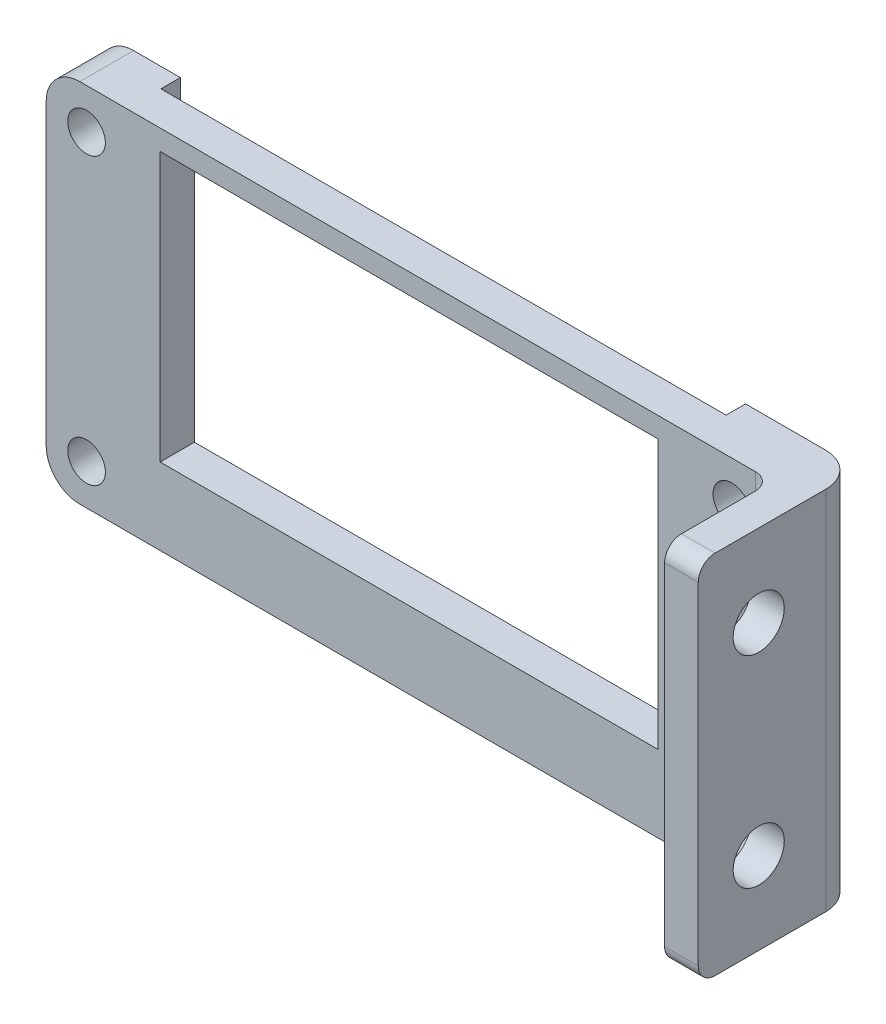
SolidWorks part; units mm, degrees
ref_plane "Front Plane" through (0, 0, 0) normal (0, 0, 1) x (1, 0, 0)
ref_plane "Top Plane" through (0, 0, 0) normal (0, 1, 0) x (1, 0, 0)
ref_plane "Right Plane" through (0, 0, 0) normal (1, 0, 0) x (0, 0, -1)
sketch "Sketch2" plane through (0, 11.515, 0) normal (0, 1, 0) x (1, 0, 0)
  line L0 (-27, 1.45) -> (-21.02, 1.45)
  line L3 (-21.02, 1.45) -> (-21.02, 0)
  line L4 (-21.02, 0) -> (21.02, 0)
  line L5 (21.02, 0) -> (21.02, 1.45)
  line L7 (21.02, 1.45) -> (29.5, 1.45)
  line L8 (-27, 1.45) -> (-27, -2.55)
  line L9 (-27, -2.55) -> (27, -2.55)
  line L10 (27, -2.55) -> (27, -10.55)
  line L11 (27, -10.55) -> (29.5, -10.55)
  line L12 (29.5, -10.55) -> (29.5, 1.45)
  point P20 (29.5695, 1.45)
  dimension "D1" = 2.5
  dimension "D2" = 4
  dimension "D3" = 12
extrude "Boss-Extrude1" add sketch "Sketch2" against normal up to surface (27.22 mm away)
sketch "Sketch1" plane through (0, 0, 0) normal (0, 0, 1) x (1, 0, 0)
  line L0 (-24.5, 11.515) -> (24.5, 11.515) construction
  line L1 (21.02, 11.515) -> (-20.98, 11.515)
  line L2 (21.02, 11.515) -> (21.02, -15.705)
  line L3 (21.02, -15.705) -> (-20.98, -15.705)
  line L4 (-20.98, 11.515) -> (-20.98, -15.705)
  line L5 (21.02, -15.705) -> (21.02, 11.515) construction
  line L6 (24.5, -15.705) -> (-24.5, -15.705) construction
  line L8 (18.525, -10) -> (-18.525, -10)
  line L9 (18.525, -10) -> (18.525, 10)
  line L10 (18.525, 10) -> (-18.525, 10)
  line L11 (-18.525, -10) -> (-18.525, 10)
  line L12 (18.525, -10) -> (-18.525, 10) construction
  line L13 (18.525, 10) -> (-18.525, -10) construction
  point P10 (0, 0)
  dimension "D1" = 42
extrude "Cut-Extrude1" cut sketch "Sketch1" against normal blind 2.5 and the other way through all contours L11 L8 L9 L10
hole_wizard "Ø2.8 (2.8) Diameter Hole1" positions "Sketch3" profile "Sketch4" hole size "Ø2.8" standard "ANSI Metric" end condition through all
sketch "Sketch3" plane through (0, 0, 2.55) normal (0, 0, 1) x (1, 0, 0)
  point P0 (24, -12.705)
  point P3 (-24, -12.705)
  point P6 (-24, 8.515)
  point P9 (24, 8.515)
sketch "Sketch4" plane through (24, -12.705, 2.55) normal (1, 0, 0) x (0, -1, 0)
  line L0 (0, 0) -> (0, 4)
  line L1 (0, 4) -> (1.4, 4)
  line L2 (1.4, 4) -> (1.4, 0)
  line L5 (1.4, 0) -> (0, 0)
  line L11 (0, -6.35) -> (0, 107.95) construction
  dimension "Thru Hole Dia." = 2.8
  dimension "Thru Hole Depth" = 4
fillet "Fillet3" radius 2.5 3 edges at (29.5, -2.095, -1.45) (-27, 11.515, 0.55) (-27, -15.705, 0.55)
fillet "Fillet4" radius 1.25 1 edges at (27, -2.095, 2.55)
hole_wizard "Ø3.8 (3.8) Diameter Hole1" positions "Sketch5" profile "Sketch6" hole size "Ø3.8" standard "ANSI Metric" end condition through all
sketch "Sketch5" plane through (29.5, 0, 0) normal (1, 0, 0) x (0, 0, -1)
  line L0 (1.45, -2.095) -> (-10.55, -2.095) construction
  line L1 (1.45, 9.015) -> (1.45, -13.205) construction
  line L2 (-10.55, -15.705) -> (-10.55, 11.515) construction
  line L4 (-6.05, -9.595) -> (-6.05, 5.405) construction
  line L6 (-1.05, -15.705) -> (-1.05, 11.515) construction
  point P14 (-6.05, -9.595)
  point P16 (-6.05, 5.405)
  point P30 (-6.05, -2.095)
  dimension "D1" = 15
  dimension "5mm" = 5
sketch "Sketch6" plane through (29.5, -9.595, 6.05) normal (0, 1, 0) x (0, 0, -1)
  line L0 (0, 0) -> (0, 56.5)
  line L1 (0, 56.5) -> (1.9, 56.5)
  line L2 (1.9, 56.5) -> (1.9, 0)
  line L5 (1.9, 0) -> (0, 0)
  line L11 (0, -6.35) -> (0, 107.95) construction
  dimension "Thru Hole Dia." = 3.8
  dimension "Thru Hole Depth" = 56.5
fillet "Fillet5" radius 1.25 2 edges at (28.25, 11.515, 10.55) (28.25, -15.705, 10.55)
